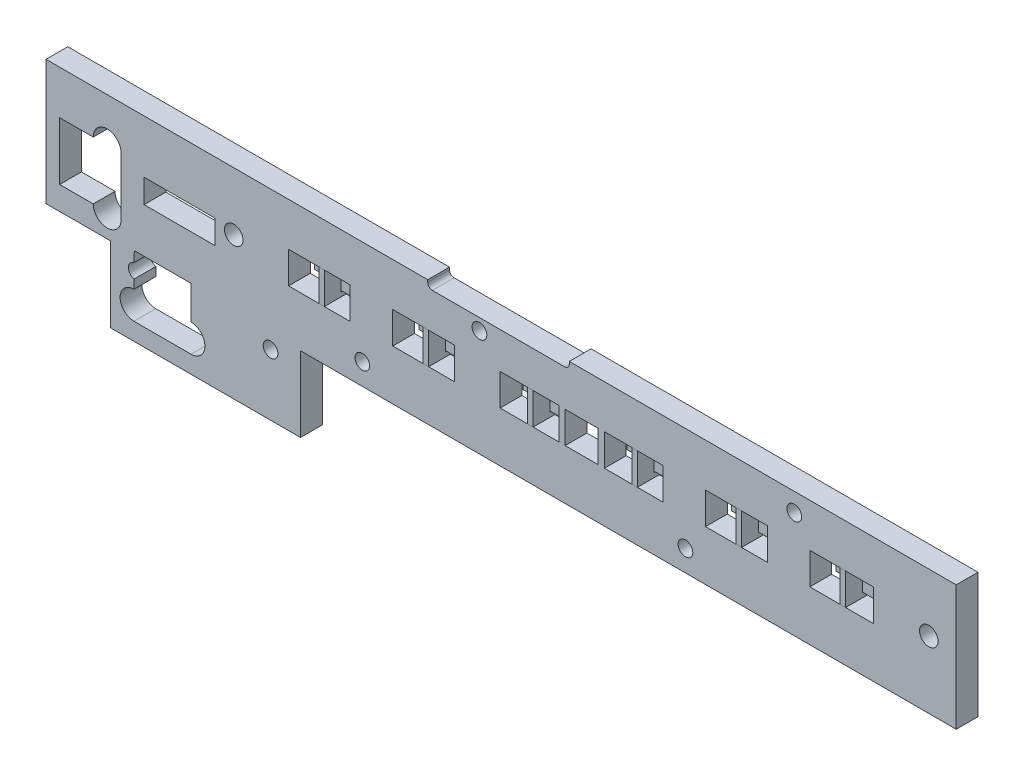
SolidWorks part; units mm, degrees
ref_plane "Front Plane" through (0, 0, 0) normal (0, 0, 1) x (1, 0, 0)
ref_plane "Top Plane" through (0, 0, 0) normal (0, 1, 0) x (1, 0, 0)
ref_plane "Right Plane" through (0, 0, 0) normal (1, 0, 0) x (0, 0, -1)
sketch "Sketch1" plane through (0, 0, 0) normal (0, 0, 1) x (1, 0, 0)
  line L1 (-97.5199, -40.1399) -> (-95.437, -40.1399)
  line L2 (-97.5199, -40.1399) -> (-97.5199, -41.3128)
  line L3 (-97.5199, -41.3128) -> (-95.437, -41.3128)
  line L4 (-95.437, -40.1399) -> (-95.437, -41.3128)
  line L5 (-92.4399, -40.1399) -> (-90.3585, -40.1399)
  line L6 (-92.4399, -40.1399) -> (-92.4399, -41.3128)
  line L7 (-92.4399, -41.3128) -> (-90.3585, -41.3128)
  line L8 (-90.3585, -40.1399) -> (-90.3585, -41.3128)
  line L9 (-75.0363, -40.1399) -> (-72.9606, -40.1399)
  line L10 (-75.0363, -40.1399) -> (-75.0363, -41.3128)
  line L11 (-75.0363, -41.3128) -> (-72.9606, -41.3128)
  line L12 (-72.9606, -40.1399) -> (-72.9606, -41.3128)
  line L13 (-69.9609, -40.1399) -> (-67.8729, -40.1399)
  line L14 (-69.9609, -40.1399) -> (-69.9609, -41.3128)
  line L15 (-69.9609, -41.3128) -> (-67.8729, -41.3128)
  line L16 (-67.8729, -40.1399) -> (-67.8729, -41.3128)
  line L17 (-52.5418, -40.1399) -> (-50.4863, -40.1399)
  line L18 (-52.5418, -40.1399) -> (-52.5418, -41.3128)
  line L19 (-52.5418, -41.3128) -> (-50.4863, -41.3128)
  line L20 (-50.4863, -40.1399) -> (-50.4863, -41.3128)
  line L21 (-47.4819, -40.1399) -> (-45.3964, -40.1399)
  line L22 (-47.4819, -40.1399) -> (-47.4819, -41.3128)
  line L23 (-47.4819, -41.3128) -> (-45.3964, -41.3128)
  line L24 (-45.3964, -40.1399) -> (-45.3964, -41.3128)
  line L25 (-30.0829, -40.1399) -> (-27.9975, -40.1399)
  line L26 (-30.0829, -40.1399) -> (-30.0829, -41.3128)
  line L27 (-30.0829, -41.3128) -> (-27.9975, -41.3128)
  line L28 (-27.9975, -40.1399) -> (-27.9975, -41.3128)
  line L29 (-24.8733, -40.1399) -> (-22.7944, -40.1399)
  line L30 (-24.8733, -40.1399) -> (-24.8733, -41.3128)
  line L31 (-24.8733, -41.3128) -> (-22.7944, -41.3128)
  line L32 (-22.7944, -40.1399) -> (-22.7944, -41.3128)
  line L33 (-7.4594, -40.1399) -> (-5.3743, -40.1399)
  line L34 (-7.4594, -40.1399) -> (-7.4594, -41.3128)
  line L35 (-7.4594, -41.3128) -> (-5.3743, -41.3128)
  line L36 (-5.3743, -40.1399) -> (-5.3743, -41.3128)
  line L37 (-2.3715, -40.1399) -> (-0.2978, -40.1399)
  line L38 (-2.3715, -40.1399) -> (-2.3715, -41.3128)
  line L39 (-2.3715, -41.3128) -> (-0.2978, -41.3128)
  line L40 (-0.2978, -40.1399) -> (-0.2978, -41.3128)
  line L41 (14.9285, -40.1399) -> (16.9943, -40.1399)
  line L42 (14.9285, -40.1399) -> (14.9285, -41.3128)
  line L43 (14.9285, -41.3128) -> (16.9943, -41.3128)
  line L44 (16.9943, -40.1399) -> (16.9943, -41.3128)
  line L45 (20.1255, -40.1399) -> (22.2118, -40.1399)
  line L46 (20.1255, -40.1399) -> (20.1255, -41.3128)
  line L47 (20.1255, -41.3128) -> (22.2118, -41.3128)
  line L48 (22.2118, -40.1399) -> (22.2118, -41.3128)
  line L49 (20.4423, -42.9104) -> (22.0728, -42.9104)
  line L50 (20.4423, -42.9104) -> (20.4423, -43.6338)
  line L51 (20.4423, -43.6338) -> (22.0728, -43.6338)
  line L52 (22.0728, -42.9104) -> (22.0728, -43.6338)
  line L53 (15.3323, -42.9104) -> (16.9094, -42.9104)
  line L54 (15.3323, -42.9104) -> (15.3323, -43.6338)
  line L55 (15.3323, -43.6338) -> (16.9094, -43.6338)
  line L56 (16.9094, -42.9104) -> (16.9094, -43.6338)
  line L57 (-7.183, -42.9104) -> (-5.7103, -42.9104)
  line L58 (-7.183, -42.9104) -> (-7.183, -43.6338)
  line L59 (-7.183, -43.6338) -> (-5.7103, -43.6338)
  line L60 (-5.7103, -42.9104) -> (-5.7103, -43.6338)
  line L61 (-2.1219, -42.9104) -> (-0.6974, -42.9104)
  line L62 (-2.1219, -42.9104) -> (-2.1219, -43.6338)
  line L63 (-2.1219, -43.6338) -> (-0.6974, -43.6338)
  line L64 (-0.6974, -42.9104) -> (-0.6974, -43.6338)
  line L65 (-24.6153, -42.9104) -> (-23.1268, -42.9104)
  line L66 (-24.6153, -42.9104) -> (-24.6153, -43.6338)
  line L67 (-24.6153, -43.6338) -> (-23.1268, -43.6338)
  line L68 (-23.1268, -42.9104) -> (-23.1268, -43.6338)
  line L69 (-29.8441, -42.9104) -> (-28.3135, -42.9104)
  line L70 (-29.8441, -42.9104) -> (-29.8441, -43.6338)
  line L71 (-29.8441, -43.6338) -> (-28.3135, -43.6338)
  line L72 (-28.3135, -42.9104) -> (-28.3135, -43.6338)
  line L73 (-47.2091, -42.9104) -> (-45.7145, -42.9104)
  line L74 (-47.2091, -42.9104) -> (-47.2091, -43.6338)
  line L75 (-47.2091, -43.6338) -> (-45.7145, -43.6338)
  line L76 (-45.7145, -42.9104) -> (-45.7145, -43.6338)
  line L77 (-52.2861, -42.9104) -> (-50.7652, -42.9104)
  line L78 (-52.2861, -42.9104) -> (-52.2861, -43.6338)
  line L79 (-52.2861, -43.6338) -> (-50.7652, -43.6338)
  line L80 (-50.7652, -42.9104) -> (-50.7652, -43.6338)
  line L81 (-74.7983, -42.9104) -> (-73.2628, -42.9104)
  line L82 (-74.7983, -42.9104) -> (-74.7983, -43.6338)
  line L83 (-74.7983, -43.6338) -> (-73.2628, -43.6338)
  line L84 (-73.2628, -42.9104) -> (-73.2628, -43.6338)
  line L85 (-69.6691, -42.9104) -> (-68.1499, -42.9104)
  line L86 (-69.6691, -42.9104) -> (-69.6691, -43.6338)
  line L87 (-69.6691, -43.6338) -> (-68.1499, -43.6338)
  line L88 (-68.1499, -42.9104) -> (-68.1499, -43.6338)
  line L89 (-97.2136, -42.9104) -> (-95.6835, -42.9104)
  line L90 (-97.2136, -42.9104) -> (-97.2136, -43.6338)
  line L91 (-97.2136, -43.6338) -> (-95.6835, -43.6338)
  line L92 (-95.6835, -42.9104) -> (-95.6835, -43.6338)
  line L93 (-92.0424, -42.9104) -> (-90.6479, -42.9104)
  line L94 (-92.0424, -42.9104) -> (-92.0424, -43.6338)
  line L95 (-92.0424, -43.6338) -> (-90.6479, -43.6338)
  line L96 (-90.6479, -42.9104) -> (-90.6479, -43.6338)
  line L97 (-40.9561, -23.8413) -> (-37.9731, -23.8413)
  line L98 (-40.9561, -23.8413) -> (-40.9561, -26.801)
  line L99 (-40.9561, -26.801) -> (-37.9731, -26.801)
  line L100 (-37.9731, -23.8413) -> (-37.9731, -26.801)
  line L101 (-27.6683, -24.3836) -> (-19.7589, -24.3836)
  line L102 (-27.6683, -24.3836) -> (-27.6683, -26.304)
  line L103 (-27.6683, -26.304) -> (-19.7589, -26.304)
  line L104 (-19.7589, -24.3836) -> (-19.7589, -26.304)
  line L105 (-10.3004, -24.5939) -> (-8.2388, -24.5939)
  line L106 (-10.3004, -24.5939) -> (-10.3004, -25.8839)
  line L107 (-10.3004, -25.8839) -> (-8.2388, -25.8839)
  line L108 (-8.2388, -24.5939) -> (-8.2388, -25.8839)
  line L109 (-108.8964, -23.5079) -> (-98.4981, -23.5079)
  line L110 (-108.8964, -23.5079) -> (-108.8964, -12.9295)
  line L111 (-108.8964, -12.9295) -> (-98.4981, -12.9295)
  line L112 (-98.4981, -23.5079) -> (-98.4981, -12.9295)
  line L113 (-96.9584, -23.5079) -> (-86.5337, -23.5079)
  line L114 (-96.9584, -23.5079) -> (-96.9584, -12.9295)
  line L115 (-96.9584, -12.9295) -> (-86.5337, -12.9295)
  line L116 (-86.5337, -23.5079) -> (-86.5337, -12.9295)
  line L118 (4.3836, -57.8006) -> (14.3835, -57.8006)
  line L119 (4.3836, -57.8006) -> (4.3836, -67.7079)
  line L120 (4.3836, -67.7079) -> (14.3835, -67.7079)
  line L121 (14.3835, -57.8006) -> (14.3835, -67.7079)
  line L122 (-95.437, -40.7263) -> (-92.4399, -40.7263) construction
  line L123 (-118.2514, 77.6271) -> (84.9486, 77.6271)
  line L124 (-118.2514, 77.6271) -> (-118.2514, -74.7729)
  line L125 (-118.2514, -74.7729) -> (84.9486, -74.7729)
  line L126 (84.9486, 77.6271) -> (84.9486, -74.7729)
  line L127 (-93.9384, -39.7294) -> (-93.9384, -44.0708) construction
  circle A0 centre (-26.6844, -66.6449) radius 1.981
  circle A1 centre (37.6626, -40.7409) radius 2
  circle A2 centre (7.2246, -15.4639) radius 1.981
  circle A3 centre (34.1156, -16.8649) radius 2
  circle A4 centre (62.0556, -16.8649) radius 2
  circle A5 centre (78.5986, -14.4479) radius 1.981
  circle A6 centre (-112.3324, -40.7459) radius 2
  circle A7 centre (-111.9014, -68.4229) radius 1.981
sketch "Sketch26" plane through (0, 0, 0) normal (0, 0, 1) x (1, 0, 0)
  line L0 (-347.4806, 59.2876) -> (-347.7663, 59.0018)
  line L5 (-126.8633, -41.6631) -> (-126.2918, -41.6631)
  line L6 (-126.2918, -41.6631) -> (-126.0061, -41.9489)
  line L8 (-126.0061, -41.9489) -> (-126.0061, -42.5204)
  line L12 (-126.0061, -42.5204) -> (-126.2918, -42.8061)
  line L14 (-126.2918, -42.8061) -> (-126.8633, -42.8061)
  line L16 (-126.8633, -42.8061) -> (-127.1491, -42.5204)
  line L17 (-127.1491, -42.5204) -> (-127.1491, -41.9489)
  line L18 (-127.1491, -41.9489) -> (-126.8633, -41.6631)
  line L19 (-124.3233, -41.6631) -> (-123.7518, -41.6631)
  line L20 (-123.7518, -41.6631) -> (-123.4661, -41.9489)
  line L21 (-123.4661, -41.9489) -> (-123.4661, -42.5204)
  line L22 (-123.4661, -42.5204) -> (-123.7518, -42.8061)
  line L23 (-123.7518, -42.8061) -> (-124.3223, -42.8061)
  line L24 (-124.3223, -42.8061) -> (-124.6091, -42.5204)
  line L25 (-124.6091, -42.5204) -> (-124.6091, -41.9489)
  line L26 (-124.6091, -41.9489) -> (-124.3233, -41.6631)
  line L28 (-121.7833, -41.6631) -> (-121.2118, -41.6631)
  line L29 (-121.2118, -41.6631) -> (-120.9261, -41.9489)
  line L30 (-120.9261, -41.9489) -> (-120.9261, -42.5204)
  line L32 (-120.9261, -42.5204) -> (-121.2118, -42.8061)
  line L34 (-121.2118, -42.8061) -> (-121.7833, -42.8061)
  line L35 (-121.7833, -42.8061) -> (-122.0691, -42.5204)
  line L36 (-122.0691, -42.5204) -> (-122.0691, -41.9489)
  line L37 (-122.0691, -41.9489) -> (-121.7833, -41.6631)
  circle A0 centre (-112.3486, -40.7056) radius 2
  circle A1 centre (37.6464, -40.7106) radius 2
sketch "Sketch2" plane through (0, 0, 0) normal (0, 0, 1) x (1, 0, 0)
  line L1 (-98.5701, -39.3785) -> (-95.299, -39.3785)
  line L2 (-98.5701, -39.3785) -> (-98.5701, -42.1823)
  line L3 (-98.5701, -42.1823) -> (-95.299, -42.1823)
  line L4 (-95.299, -39.3785) -> (-95.299, -42.1823)
  line L5 (-94.4404, -38.3353) -> (-89.1697, -38.3353)
  line L6 (-94.4404, -38.3353) -> (-94.4404, -43.2582)
  line L7 (-94.4404, -43.2582) -> (-89.1697, -43.2582)
  line L8 (-89.1697, -38.3353) -> (-89.1697, -43.2582)
  line L9 (-76.0896, -39.3785) -> (-72.8441, -39.3785)
  line L10 (-76.0896, -39.3785) -> (-76.0896, -42.1823)
  line L11 (-76.0896, -42.1823) -> (-72.8441, -42.1823)
  line L12 (-72.8441, -39.3785) -> (-72.8441, -42.1823)
  line L13 (-71.9827, -38.3353) -> (-66.6627, -38.3353)
  line L14 (-71.9827, -38.3353) -> (-71.9827, -43.2582)
  line L15 (-71.9827, -43.2582) -> (-66.6627, -43.2582)
  line L16 (-66.6627, -38.3353) -> (-66.6627, -43.2582)
  line L17 (-53.6202, -39.3785) -> (-50.3601, -39.3785)
  line L18 (-53.6202, -39.3785) -> (-53.6202, -42.1823)
  line L19 (-53.6202, -42.1823) -> (-50.3601, -42.1823)
  line L20 (-50.3601, -39.3785) -> (-50.3601, -42.1823)
  line L21 (-49.5184, -38.3353) -> (-44.1883, -38.3353)
  line L22 (-49.5184, -38.3353) -> (-49.5184, -43.2582)
  line L23 (-49.5184, -43.2582) -> (-44.1883, -43.2582)
  line L24 (-44.1883, -38.3353) -> (-44.1883, -43.2582)
  line L25 (-31.1243, -39.3785) -> (-27.8326, -39.3785)
  line L26 (-31.1243, -39.3785) -> (-31.1243, -42.1823)
  line L27 (-31.1243, -42.1823) -> (-27.8326, -42.1823)
  line L28 (-27.8326, -39.3785) -> (-27.8326, -42.1823)
  line L29 (-27.0038, -38.3353) -> (-21.7574, -38.3353)
  line L30 (-27.0038, -38.3353) -> (-27.0038, -43.2582)
  line L31 (-27.0038, -43.2582) -> (-21.7574, -43.2582)
  line L32 (-21.7574, -38.3353) -> (-21.7574, -43.2582)
  line L33 (-8.6176, -39.3785) -> (-5.1948, -39.3785)
  line L34 (-8.6176, -39.3785) -> (-8.6176, -42.3426)
  line L35 (-8.6176, -42.3426) -> (-5.1948, -42.3426)
  line L36 (-5.1948, -39.3785) -> (-5.1948, -42.3426)
  line L37 (-4.443, -38.4846) -> (0.8593, -38.4846)
  line L38 (-4.443, -38.4846) -> (-4.443, -43.3911)
  line L39 (-4.443, -43.3911) -> (0.8593, -43.3911)
  line L40 (0.8593, -38.4846) -> (0.8593, -43.3911)
  line L41 (13.9171, -39.6123) -> (17.1222, -39.6123)
  line L42 (13.9171, -39.6123) -> (13.9171, -42.3426)
  line L43 (13.9171, -42.3426) -> (17.1222, -42.3426)
  line L44 (17.1222, -39.6123) -> (17.1222, -42.3426)
  line L45 (18.0465, -38.4846) -> (23.3015, -38.4846)
  line L46 (18.0465, -38.4846) -> (18.0465, -43.3911)
  line L47 (18.0465, -43.3911) -> (23.3015, -43.3911)
  line L48 (23.3015, -38.4846) -> (23.3015, -43.3911)
  circle A0 centre (-112.3324, -40.7459) radius 2
  circle A1 centre (37.6626, -40.7409) radius 2
sketch "Sketch3" plane through (0, 0, 0) normal (0, 0, 1) x (1, 0, 0)
  line L0 (-92.4239, -40.172) -> (-90.3528, -40.172)
  line L1 (-117.3165, -28.7781) -> (77.6835, -28.7781)
  line L2 (-117.3165, -28.7781) -> (-117.3165, -54.7781)
  line L3 (-117.3165, -54.7781) -> (77.6835, -54.7781)
  line L4 (77.6835, -28.7781) -> (77.6835, -54.7781)
  line L5 (-97.501, -40.1688) -> (-95.4364, -40.1688)
  line L6 (-97.501, -40.1688) -> (-97.501, -41.3458)
  line L7 (-97.501, -41.3458) -> (-95.4364, -41.3458)
  line L8 (-95.4364, -40.1688) -> (-95.4364, -41.3458)
  line L9 (-92.4239, -40.172) -> (-92.4239, -41.3431)
  line L10 (-92.4239, -41.3431) -> (-90.3528, -41.3431)
  line L11 (-90.3528, -40.172) -> (-90.3528, -41.3431)
  line L12 (-75.0249, -40.172) -> (-72.9538, -40.172)
  line L13 (-75.0249, -40.172) -> (-75.0249, -41.3431)
  line L14 (-75.0249, -41.3431) -> (-72.9538, -41.3431)
  line L15 (-72.9538, -40.172) -> (-72.9538, -41.3431)
  line L16 (-69.9449, -40.172) -> (-67.8738, -40.172)
  line L17 (-69.9449, -40.172) -> (-69.9449, -41.3431)
  line L18 (-69.9449, -41.3431) -> (-67.8738, -41.3431)
  line L19 (-67.8738, -40.172) -> (-67.8738, -41.3431)
  line L20 (-52.5459, -40.172) -> (-50.4749, -40.172)
  line L21 (-52.5459, -40.172) -> (-52.5459, -41.3431)
  line L22 (-52.5459, -41.3431) -> (-50.4749, -41.3431)
  line L23 (-50.4749, -40.172) -> (-50.4749, -41.3431)
  line L24 (20.0981, -40.172) -> (22.1692, -40.172)
  line L25 (20.0981, -40.172) -> (20.0981, -41.3431)
  line L26 (20.0981, -41.3431) -> (22.1692, -41.3431)
  line L27 (22.1692, -40.172) -> (22.1692, -41.3431)
  line L28 (14.8911, -40.172) -> (16.9622, -40.172)
  line L29 (14.8911, -40.172) -> (14.8911, -41.3431)
  line L30 (14.8911, -41.3431) -> (16.9622, -41.3431)
  line L31 (16.9622, -40.172) -> (16.9622, -41.3431)
  line L32 (-7.4609, -40.172) -> (-5.3898, -40.172)
  line L33 (-7.4609, -40.172) -> (-7.4609, -41.3431)
  line L34 (-7.4609, -41.3431) -> (-5.3898, -41.3431)
  line L35 (-5.3898, -40.172) -> (-5.3898, -41.3431)
  line L36 (-2.3809, -40.172) -> (-0.3098, -40.172)
  line L37 (-2.3809, -40.172) -> (-2.3809, -41.3431)
  line L38 (-2.3809, -41.3431) -> (-0.3098, -41.3431)
  line L39 (-0.3098, -40.172) -> (-0.3098, -41.3431)
  line L40 (-30.0669, -40.172) -> (-27.9959, -40.172)
  line L41 (-30.0669, -40.172) -> (-30.0669, -41.3431)
  line L42 (-30.0669, -41.3431) -> (-27.9959, -41.3431)
  line L43 (-27.9959, -40.172) -> (-27.9959, -41.3431)
  line L44 (-24.8599, -40.172) -> (-22.7889, -40.172)
  line L45 (-24.8599, -40.172) -> (-24.8599, -41.3431)
  line L46 (-24.8599, -41.3431) -> (-22.7889, -41.3431)
  line L47 (-22.7889, -40.172) -> (-22.7889, -41.3431)
  line L48 (-47.4659, -40.172) -> (-45.3838, -40.172)
  line L49 (-47.4659, -40.172) -> (-47.4659, -41.359)
  line L50 (-47.4659, -41.359) -> (-45.3838, -41.359)
  line L51 (-45.3838, -40.172) -> (-45.3838, -41.359)
  line L53 (-97.7776, -39.3992) -> (-94.4929, -39.3992)
  line L54 (-97.7776, -39.3992) -> (-97.7776, -42.1711)
  line L55 (-97.7776, -42.1711) -> (-94.4929, -42.1711)
  line L56 (-94.4929, -39.3992) -> (-94.4929, -42.1711)
  line L57 (-93.627, -38.3011) -> (-88.3259, -38.3011)
  line L58 (-93.627, -38.3011) -> (-93.627, -43.2774)
  line L59 (-93.627, -43.2774) -> (-88.3259, -43.2774)
  line L60 (-88.3259, -38.3011) -> (-88.3259, -43.2774)
  line L65 (-75.2412, -39.3992) -> (-72.0308, -39.3992)
  line L66 (-75.2412, -39.3992) -> (-75.2412, -42.1711)
  line L67 (-75.2412, -42.1711) -> (-72.0308, -42.1711)
  line L68 (-72.0308, -39.3992) -> (-72.0308, -42.1711)
  line L69 (-71.1042, -38.3011) -> (-65.8448, -38.3011)
  line L70 (-71.1042, -38.3011) -> (-71.1042, -43.2774)
  line L71 (-71.1042, -43.2774) -> (-65.8448, -43.2774)
  line L72 (-65.8448, -38.3011) -> (-65.8448, -43.2774)
  line L73 (-52.7841, -39.3992) -> (-49.488, -39.3992)
  line L74 (-52.7841, -39.3992) -> (-52.7841, -42.1711)
  line L75 (-52.7841, -42.1711) -> (-49.488, -42.1711)
  line L76 (-49.488, -39.3992) -> (-49.488, -42.1711)
  line L77 (-48.6647, -38.3011) -> (-43.2769, -38.3011)
  line L78 (-48.6647, -38.3011) -> (-48.6647, -43.2774)
  line L79 (-48.6647, -43.2774) -> (-43.2769, -43.2774)
  line L80 (-43.2769, -38.3011) -> (-43.2769, -43.2774)
  line L81 (-30.2826, -39.3992) -> (-26.9885, -39.3992)
  line L82 (-30.2826, -39.3992) -> (-30.2826, -42.1711)
  line L83 (-30.2826, -42.1711) -> (-26.9885, -42.1711)
  line L84 (-26.9885, -39.3992) -> (-26.9885, -42.1711)
  line L85 (-26.1225, -38.3011) -> (-20.7991, -38.3011)
  line L86 (-26.1225, -38.3011) -> (-26.1225, -43.2774)
  line L87 (-26.1225, -43.2774) -> (-20.7991, -43.2774)
  line L88 (-20.7991, -38.3011) -> (-20.7991, -43.2774)
  line L89 (-7.7852, -39.3992) -> (-4.5112, -39.3992)
  line L90 (-7.7852, -39.3992) -> (-7.7852, -42.1711)
  line L91 (-7.7852, -42.1711) -> (-4.5112, -42.1711)
  line L92 (-4.5112, -39.3992) -> (-4.5112, -42.1711)
  line L93 (-3.6465, -38.3011) -> (1.6758, -38.3011)
  line L94 (-3.6465, -38.3011) -> (-3.6465, -43.2774)
  line L95 (-3.6465, -43.2774) -> (1.6758, -43.2774)
  line L96 (1.6758, -38.3011) -> (1.6758, -43.2774)
  line L97 (14.7148, -39.3992) -> (17.9992, -39.3992)
  line L98 (14.7148, -39.3992) -> (14.7148, -42.1711)
  line L99 (14.7148, -42.1711) -> (17.9992, -42.1711)
  line L100 (17.9992, -39.3992) -> (17.9992, -42.1711)
  line L101 (18.8348, -38.3011) -> (24.1792, -38.3011)
  line L102 (18.8348, -38.3011) -> (18.8348, -43.2774)
  line L103 (18.8348, -43.2774) -> (24.1792, -43.2774)
  line L104 (24.1792, -38.3011) -> (24.1792, -43.2774)
  circle A0 centre (-112.3165, -40.7781) radius 2
  circle A1 centre (37.6835, -40.7781) radius 2
extrude "Boss-Extrude1" add sketch "Sketch3" along normal blind 0.5 contours L60 L57 L58 L59 L0 L11 L10 L9 | L56 L53 L54 L55 L5 L8 L7 L6 | L68 L65 L66 L67 L12 L15 L14 L13 | L72 L69 L70 L71 L16 L19 L18 L17 | L76 L73 L74 L75 L20 L23 L22 L21 | L80 L77 L78 L79 L48 L51 L50 L49 | L84 L81 L82 L83 L40 L43 L42 L41 | L88 L85 L86 L87 L44 L47 L46 L45 | L92 L89 L90 L91 L32 L35 L34 L33 | L96 L93 L94 L95 L36 L39 L38 L37 | L100 L97 L98 L99 L28 L31 L30 L29 | L104 L101 L102 L103 L24 L27 L26 L25
extrude "Boss-Extrude2" add sketch "Sketch2" along normal blind 1 contours L2 L1 L4 L3 | L6 L5 L8 L7 | L10 L9 L12 L11 | L14 L13 L16 L15 | L18 L17 L20 L19 | L22 L21 L24 L23 | L26 L25 L28 L27 | L30 L29 L32 L31 | L34 L33 L36 L35 | L38 L37 L40 L39 | L42 L41 L44 L43 | L46 L45 L48 L47
sketch "Sketch27" plane through (0, 0, 0) normal (0, 0, 1) x (1, 0, 0)
  line L6 (-127.1316, -41.9504) -> (-126.8458, -41.6646)
  line L7 (-126.8458, -41.6646) -> (-126.2743, -41.6646)
  line L8 (-126.2743, -41.6646) -> (-125.9886, -41.9504)
  line L9 (-125.9886, -41.9504) -> (-125.9886, -42.5219)
  line L10 (-125.9886, -42.5219) -> (-126.2743, -42.8076)
  line L11 (-126.2743, -42.8076) -> (-126.8458, -42.8076)
  line L12 (-126.8458, -42.8076) -> (-127.1316, -42.5219)
  line L13 (-127.1316, -42.5219) -> (-127.1316, -41.9504)
  line L14 (-124.3058, -41.6646) -> (-123.7343, -41.6646)
  line L15 (-123.7343, -41.6646) -> (-123.4486, -41.9504)
  line L16 (-123.4486, -41.9504) -> (-123.4486, -42.5219)
  line L17 (-123.4486, -42.5219) -> (-123.7343, -42.8076)
  line L18 (-123.7343, -42.8076) -> (-124.3058, -42.8076)
  line L19 (-124.3058, -42.8076) -> (-124.5916, -42.5219)
  line L20 (-124.5916, -42.5219) -> (-124.5916, -41.9504)
  line L21 (-124.5916, -41.9504) -> (-124.3058, -41.6646)
  line L22 (-122.0516, -41.9504) -> (-121.7658, -41.6646)
  line L23 (-121.7658, -41.6646) -> (-121.1943, -41.6646)
  line L24 (-121.1943, -41.6646) -> (-120.9086, -41.9504)
  line L25 (-120.9086, -41.9504) -> (-120.9086, -42.5219)
  line L26 (-120.9086, -42.5219) -> (-121.1943, -42.8076)
  line L27 (-121.1943, -42.8076) -> (-121.7658, -42.8076)
  line L28 (-121.7658, -42.8076) -> (-122.0516, -42.5219)
  line L29 (-122.0516, -42.5219) -> (-122.0516, -41.9504)
  circle A1 centre (-112.3361, -40.7121) radius 2
  circle A2 centre (37.6639, -40.7121) radius 2
sketch "Sketch4" plane through (0, 0, 0) normal (0, 0, 1) x (1, 0, 0)
  line L0 (-39.4646, -26.801) -> (-138.2561, -26.801) construction
  line L1 (-40.9561, -26.801) -> (-37.9731, -26.801) construction
  line L2 (-118.2514, 77.6271) -> (-118.2514, -74.7729) construction
  line L3 (-39.4646, -26.801) -> (84.9486, -26.801) construction
  line L5 (-118.2514, -57.8006) -> (84.9486, -57.8006) construction
  line L6 (-88.3259, -38.3011) -> (-118.2514, -38.3011) construction
  line L7 (-88.3259, -38.3011) -> (84.9486, -38.3011) construction
  line L8 (23.3015, -43.3911) -> (84.9486, -43.3911) construction
  line L9 (23.3015, -43.3911) -> (-118.2514, -43.3911) construction
  line L10 (-97.2136, -43.6338) -> (-118.2514, -43.6338) construction
  line L11 (-97.2136, -43.6338) -> (84.9486, -43.6338) construction
  line L12 (-114.3324, -40.7459) -> (-118.2514, -40.7459) construction
  line L13 (-110.3324, -40.7459) -> (-98.5701, -40.7804) construction
  line L14 (-98.5701, -39.3785) -> (-98.5701, -42.1823) construction
  line L15 (35.6626, -40.7409) -> (24.2584, -40.7409) construction
  line L16 (39.6626, -40.7409) -> (44.6626, -40.7409) construction
  line L17 (-24.3806, -38.3353) -> (-24.3806, -28.3353) construction
  line L18 (-27.0038, -38.3353) -> (-21.7574, -38.3353) construction
  line L19 (-20.7991, -38.3011) -> (-20.7991, -31.3011) construction
  line L20 (-24.3806, -43.6338) -> (-24.3806, -53.6338) construction
  line L21 (-20.7991, -43.6338) -> (-20.7991, -50.6338) construction
  line L22 (-31.1243, -40.7804) -> (-34.1243, -40.7804) construction
  line L23 (-31.1243, -39.3785) -> (-31.1243, -42.1823) construction
  line L24 (-20.7991, -40.7893) -> (-17.7991, -40.7893) construction
  line L25 (-20.7991, -38.3011) -> (-20.7991, -43.2774) construction
  line L26 (-43.2769, -40.7893) -> (-40.2769, -40.7893) construction
  line L27 (-43.2769, -38.3011) -> (-43.2769, -43.2774) construction
  line L28 (-53.6202, -40.7804) -> (-56.6202, -40.7804) construction
  line L29 (-53.6202, -39.3785) -> (-53.6202, -42.1823) construction
  line L30 (-8.6176, -40.8606) -> (-11.6176, -40.8606) construction
  line L31 (-8.6176, -39.3785) -> (-8.6176, -42.3426) construction
  line L32 (1.6758, -40.7893) -> (4.6755, -40.8345) construction
  line L33 (1.6758, -38.3011) -> (1.6758, -43.2774) construction
  line L34 (13.9171, -40.9774) -> (10.9171, -40.9774) construction
  line L35 (13.9171, -39.6123) -> (13.9171, -42.3426) construction
  line L36 (24.1792, -40.218) -> (27.1792, -40.218) construction
  line L37 (24.1792, -38.3011) -> (24.1792, -43.2774) construction
  line L38 (-98.5701, -39.9285) -> (-101.5701, -39.9285) construction
  line L39 (-88.3259, -40.7893) -> (-85.3259, -40.7893) construction
  line L40 (-88.3259, -38.3011) -> (-88.3259, -43.2774) construction
  line L41 (-76.0896, -40.7804) -> (-79.0896, -40.7804) construction
  line L42 (-76.0896, -39.3785) -> (-76.0896, -42.1823) construction
  line L43 (-65.8448, -40.7893) -> (-62.8455, -40.8558) construction
  line L44 (-65.8448, -38.3011) -> (-65.8448, -43.2774) construction
  line L46 (-17.7991, -31.3011) -> (-34.1243, -31.3011)
  line L47 (-17.7991, -31.3011) -> (-17.7991, -50.9192)
  line L48 (-17.7991, -50.9192) -> (-34.1243, -50.9192)
  line L49 (-34.1243, -31.3011) -> (-34.1243, -50.9192)
  line L50 (-40.2769, -31.3011) -> (-56.6202, -31.3011)
  line L51 (-40.2769, -31.3011) -> (-40.2769, -50.6338)
  line L52 (-40.2769, -50.6338) -> (-56.6202, -50.6338)
  line L53 (-56.6202, -31.3011) -> (-56.6202, -50.6338)
  line L54 (-62.8455, -31.3011) -> (-79.0896, -31.3011)
  line L55 (-62.8455, -31.3011) -> (-62.8455, -50.6338)
  line L56 (-62.8455, -50.6338) -> (-79.0896, -50.6338)
  line L57 (-79.0896, -31.3011) -> (-79.0896, -50.6338)
  line L58 (-85.3259, -31.3011) -> (-101.5701, -31.3011)
  line L59 (-85.3259, -31.3011) -> (-85.3259, -50.6338)
  line L60 (-85.3259, -50.6338) -> (-101.5701, -50.6338)
  line L61 (-101.5701, -31.3011) -> (-101.5701, -50.6338)
  line L66 (-11.6176, -31.3011) -> (4.6755, -31.3011)
  line L67 (-11.6176, -31.3011) -> (-11.6176, -50.9192)
  line L68 (-11.6176, -50.9192) -> (4.6755, -50.9192)
  line L69 (4.6755, -31.3011) -> (4.6755, -50.9192)
  line L70 (10.9171, -31.3011) -> (27.1792, -31.3011)
  line L71 (10.9171, -31.3011) -> (10.9171, -50.9192)
  line L72 (10.9171, -50.9192) -> (27.1792, -50.9192)
  line L73 (27.1792, -31.3011) -> (27.1792, -50.9192)
  line L74 (-118.2514, -28.2107) -> (43.5826, -28.2107)
  line L77 (43.5826, -28.2107) -> (43.5826, -55.2138)
  line L79 (-152.8489, -71.4364) -> (-152.8489, -28.2107)
  line L80 (-152.8489, -71.4364) -> (-97.9233, -71.4364)
  line L81 (43.5826, -55.2138) -> (-97.9233, -55.2138)
  line L82 (-97.9233, -55.2138) -> (-97.9233, -71.4364)
  line L83 (-152.8489, -28.2107) -> (-118.2514, -28.2107)
  circle A0 centre (-112.3324, -40.7459) radius 2
  circle A1 centre (37.6626, -40.7409) radius 2
  circle A2 centre (-112.3324, -40.7459) radius 2
  circle A3 centre (37.6626, -40.7409) radius 2
  point P127 (-98.406, -55.2138)
  point P128 (-118.2514, -35.8832)
extrude "Boss-Extrude3" add sketch "Sketch4" along normal blind 4.7 separate body contours L74 L77 L81 L82 L80 L79 L83
sketch "Sketch6" plane through (0, 0, 0) normal (0, 0, 1) x (1, 0, 0)
  line L3 (-39.4646, -26.801) -> (84.9486, -26.801) construction
  line L12 (-114.3324, -40.7459) -> (-118.2514, -40.7459) construction
  line L16 (39.6626, -40.7409) -> (44.6626, -40.7409) construction
  line L46 (-19.6893, -37.55) -> (-32.3365, -37.55)
  line L47 (-19.6893, -37.55) -> (-19.6893, -44.39)
  line L48 (-19.6893, -44.39) -> (-32.3365, -44.39)
  line L49 (-32.3365, -37.55) -> (-32.3365, -44.39)
  line L50 (-42.1847, -37.55) -> (-54.8514, -37.55)
  line L51 (-42.1847, -37.55) -> (-42.1847, -44.39)
  line L52 (-42.1847, -44.39) -> (-54.8514, -44.39)
  line L53 (-54.8514, -37.55) -> (-54.8514, -44.39)
  line L54 (-64.6621, -37.55) -> (-78.0238, -37.55)
  line L55 (-64.6621, -37.55) -> (-64.6621, -44.39)
  line L56 (-64.6621, -44.39) -> (-78.0238, -44.39)
  line L57 (-78.0238, -37.55) -> (-78.0238, -44.39)
  line L58 (-87.1961, -37.55) -> (-100.5057, -37.55)
  line L59 (-87.1961, -37.55) -> (-87.1961, -44.39)
  line L60 (-87.1961, -44.39) -> (-100.5057, -44.39)
  line L61 (-100.5057, -37.55) -> (-100.5057, -44.39)
  line L66 (-10.5159, -37.55) -> (2.8408, -37.55)
  line L67 (-10.5159, -37.55) -> (-10.5159, -44.39)
  line L68 (-10.5159, -44.39) -> (2.8408, -44.39)
  line L69 (2.8408, -37.55) -> (2.8408, -44.39)
  line L70 (11.9869, -37.55) -> (25.7171, -37.55)
  line L71 (11.9869, -37.55) -> (11.9869, -44.39)
  line L72 (11.9869, -44.39) -> (25.7171, -44.39)
  line L73 (25.7171, -37.55) -> (25.7171, -44.39)
  line L74 (-118.2514, -28.3353) -> (44.6626, -28.3353)
  line L75 (-118.2514, -28.3353) -> (-118.2514, -53.6338)
  line L76 (-118.2514, -53.6338) -> (44.6626, -53.6338)
  line L77 (44.6626, -28.3353) -> (44.6626, -53.6338)
  circle A0 centre (-112.3324, -40.7459) radius 2
  circle A1 centre (37.6626, -40.7409) radius 2
  circle A2 centre (-112.3324, -40.7459) radius 2
  circle A3 centre (37.6626, -40.7409) radius 2
extrude "Cut-Extrude7" cut sketch "Sketch6" against normal through all and the other way through all contours L58 L61 L60 L59 | L55 L54 L57 L56 | L51 L50 L53 L52 | L47 L46 L49 L48 | L67 L66 L69 L68 | L71 L70 L73 L72 | A3 | A0
sketch "Sketch7" plane through (0, 0, 0) normal (0, 0, 1) x (1, 0, 0)
  circle A0 centre (-112.3324, -40.7459) radius 2
sketch "Sketch16" plane through (0, 0, 4.7) normal (0, 0, 1) x (1, 0, 0)
  line L0 (-94.3979, -43.4496) -> (-92.7752, -43.4496) construction
  line L1 (-92.7752, -37.55) -> (-93.9752, -37.55)
  line L2 (-92.7752, -37.55) -> (-92.7752, -44.39)
  line L3 (-92.7752, -44.39) -> (-93.9752, -44.39)
  line L4 (-93.9752, -37.55) -> (-93.9752, -44.39)
  line L5 (-64.6621, -44.39) -> (-78.0238, -44.39) construction
  line L6 (-94.3979, -38.038) -> (-92.7752, -38.038) construction
  line L7 (-71.479, -44.39) -> (-70.279, -44.39)
  line L8 (-71.479, -44.39) -> (-71.479, -37.55)
  line L9 (-71.479, -37.55) -> (-70.279, -37.55)
  line L10 (-70.279, -44.39) -> (-70.279, -37.55)
  line L11 (-64.6621, -37.55) -> (-78.0238, -37.55) construction
  line L12 (-71.479, -43.4496) -> (-49.5779, -43.4496) construction
  line L14 (-48.9237, -44.39) -> (-47.7237, -44.39)
  line L15 (-48.9237, -44.39) -> (-48.9237, -37.55)
  line L16 (-48.9237, -37.55) -> (-47.7237, -37.55)
  line L17 (-47.7237, -44.39) -> (-47.7237, -37.55)
  line L19 (-49.5779, -43.4496) -> (-27.1679, -43.4496) construction
  line L21 (-26.4201, -44.39) -> (-25.2201, -44.39)
  line L22 (-26.4201, -44.39) -> (-26.4201, -37.55)
  line L23 (-26.4201, -37.55) -> (-25.2201, -37.55)
  line L24 (-25.2201, -44.39) -> (-25.2201, -37.55)
  line L26 (-27.1679, -43.4496) -> (-4.7579, -43.4496) construction
  line L27 (-10.5159, -44.39) -> (2.8408, -44.39) construction
  line L28 (-3.9378, -44.39) -> (-2.7378, -44.39)
  line L29 (-3.9378, -44.39) -> (-3.9378, -37.55)
  line L30 (-3.9378, -37.55) -> (-2.7378, -37.55)
  line L31 (-2.7378, -44.39) -> (-2.7378, -37.55)
  line L32 (-10.5159, -37.55) -> (2.8408, -37.55) construction
  line L33 (-4.7579, -43.4496) -> (17.6521, -43.4496) construction
  line L34 (11.9869, -44.39) -> (25.7171, -44.39) construction
  line L35 (18.5159, -44.39) -> (19.7159, -44.39)
  line L36 (18.5159, -44.39) -> (18.5159, -37.55)
  line L37 (18.5159, -37.55) -> (19.7159, -37.55)
  line L38 (19.7159, -44.39) -> (19.7159, -37.55)
  line L39 (11.9869, -37.55) -> (25.7171, -37.55) construction
extrude "Boss-Extrude10" add sketch "Sketch16" against normal blind 4.7 separate body
sketch "Sketch18" plane through (0, 0, 0) normal (0, 0, 1) x (1, 0, 0)
  line L11 (-92.7752, -38.0383) -> (-92.7752, -43.4497)
  line L13 (-93.9752, -38.0383) -> (-93.9752, -43.4497)
sketch "Sketch20" plane through (0, 0, 4.7) normal (0, 0, 1) x (1, 0, 0)
  line L7 (-71.479, -38.0881) -> (-71.479, -43.4497)
  line L9 (-70.279, -38.0881) -> (-70.279, -43.4497)
  line L12 (-48.9237, -38.0881) -> (-47.7237, -38.0881)
  line L14 (-48.9237, -43.4497) -> (-47.7237, -43.4497)
  line L18 (-26.4201, -38.0881) -> (-25.2201, -38.0881)
  line L19 (-26.4201, -38.0881) -> (-26.4201, -43.4497)
  line L20 (-26.4201, -43.4497) -> (-25.2201, -43.4497)
  line L21 (-25.2201, -38.0881) -> (-25.2201, -43.4497)
  line L24 (-3.9378, -38.0881) -> (-2.7378, -38.0881)
  line L25 (-3.9378, -38.0881) -> (-3.9378, -43.4497)
  line L26 (-3.9378, -43.4497) -> (-2.7378, -43.4497)
  line L27 (-2.7378, -38.0881) -> (-2.7378, -43.4497)
  line L30 (18.5159, -38.4521) -> (19.7159, -38.4521)
  line L31 (18.5159, -38.4521) -> (18.5159, -43.4497)
  line L32 (18.5159, -43.4497) -> (19.7159, -43.4497)
  line L33 (19.7159, -38.4521) -> (19.7159, -43.4497)
sketch "Sketch30" plane through (0, 0, 4.7) normal (0, 0, 1) x (1, 0, 0)
  line L21 (-131.6825, -39.6725) -> (-116.388, -39.6725)
  line L22 (-131.6825, -39.6725) -> (-131.6825, -44.7976)
  line L23 (-131.6825, -44.7976) -> (-116.388, -44.7976)
  line L24 (-116.388, -39.6725) -> (-116.388, -44.7976)
extrude "Cut-Extrude15" cut sketch "Sketch30" against normal blind 10 contours L22 L23 L24 L21
sketch "Sketch33" plane through (0, 0, 0) normal (0, 0, 1) x (1, 0, 0)
  line L0 (-152.8489, -71.4364) -> (-97.9233, -71.4364) construction
  line L1 (-138.9216, -71.4364) -> (-152.8489, -71.4364)
  line L2 (-138.9216, -71.4364) -> (-138.9216, -55.187)
  line L3 (-138.9216, -55.187) -> (-152.8489, -55.187)
  line L4 (-152.8489, -71.4364) -> (-152.8489, -55.187)
  line L5 (-152.8489, -71.4364) -> (-152.8489, -28.2107) construction
extrude "Cut-Extrude17" cut sketch "Sketch33" along normal blind 10
sketch "Sketch34" plane through (-55.9596, -56.2386, 5.9303) normal (0, 0, -1) x (-1, 0, 0)
  line L0 (80.6965, 18.5874) -> (80.6965, 5.9473)
  line L3 (65.5953, -11.4419) -> (77.8953, -11.4419)
  line L4 (65.5953, -6.8669) -> (65.5953, -10.0169) construction
  line L5 (77.8953, -10.0169) -> (77.8953, -6.8669) construction
  line L6 (65.5953, -5.4419) -> (65.5953, 1.801)
  line L7 (65.5953, 1.801) -> (77.8417, 1.801)
  line L8 (77.8417, 1.801) -> (77.8953, -5.4419)
  line L9 (86.6965, 18.5875) -> (93.9465, 18.5875)
  line L10 (86.6965, 6.098) -> (93.9465, 6.098)
  line L11 (93.9465, 6.098) -> (93.9465, 18.5875)
  arc A4 (80.6965, 18.5874) -> (86.6965, 18.5875) centre (83.6965, 18.626) cw
  arc A5 (80.6965, 5.9473) -> (86.6965, 6.098) centre (83.6946, 6.098) ccw
  arc A6 (77.8953, -5.4419) -> (77.8953, -11.4419) centre (77.8953, -8.4419) cw
  arc A7 (65.5953, -5.4419) -> (65.5953, -11.4419) centre (65.5953, -8.4419) ccw
extrude "Cut-Extrude19" cut sketch "Sketch34" along normal blind 10
sketch "Sketch36" plane through (0, 0, 0) normal (0, 0, -1) x (-1, 0, 0)
  line L1 (-19.7159, -38.4521) -> (-18.5159, -38.4521)
  line L2 (-19.7159, -38.4521) -> (-19.7159, -43.4497)
  line L3 (-19.7159, -43.4497) -> (-18.5159, -43.4497)
  line L4 (-18.5159, -38.4521) -> (-18.5159, -43.4497)
  line L5 (2.7378, -38.0881) -> (3.9378, -38.0881)
  line L6 (2.7378, -38.0881) -> (2.7378, -43.4497)
  line L7 (2.7378, -43.4497) -> (3.9378, -43.4497)
  line L8 (3.9378, -38.0881) -> (3.9378, -43.4497)
  line L9 (26.4201, -38.0881) -> (25.2201, -38.0881)
  line L10 (26.4201, -38.0881) -> (26.4201, -43.4497)
  line L11 (26.4201, -43.4497) -> (25.2201, -43.4497)
  line L12 (25.2201, -38.0881) -> (25.2201, -43.4497)
  line L13 (48.9237, -38.0881) -> (47.7237, -38.0881)
  line L14 (48.9237, -38.0881) -> (48.9237, -43.4497)
  line L15 (48.9237, -43.4497) -> (47.7237, -43.4497)
  line L16 (47.7237, -38.0881) -> (47.7237, -43.4497)
  line L17 (71.479, -38.0881) -> (70.279, -38.0881)
  line L18 (71.479, -38.0881) -> (71.479, -43.4497)
  line L19 (71.479, -43.4497) -> (70.279, -43.4497)
  line L20 (70.279, -38.0881) -> (70.279, -43.4497)
  line L21 (93.9752, -38.0383) -> (92.7752, -38.0383)
  line L22 (93.9752, -38.0383) -> (93.9752, -43.4497)
  line L23 (93.9752, -43.4497) -> (92.7752, -43.4497)
  line L24 (92.7752, -38.0383) -> (92.7752, -43.4497)
extrude "Cut-Extrude23" cut sketch "Sketch36" against normal blind 1.1
sketch "Sketch37" plane through (-55.9596, -56.2386, 5.9303) normal (0, 0, -1) x (-1, 0, 0)
  line L1 (-22.1877, 18.6333) -> (-15.1423, 18.6333)
  line L2 (-22.1877, 18.6333) -> (-22.1877, 11.8479)
  line L3 (-22.1877, 11.8479) -> (-15.1423, 11.8479)
  line L4 (-15.1423, 18.6333) -> (-15.1423, 11.8479)
extrude "Cut-Extrude28" cut sketch "Sketch37" along normal through all
sketch "Sketch41" plane through (-55.9596, -56.2386, 5.9303) normal (0, 0, -1) x (-1, 0, 0)
  circle A0 centre (77.513, -1.989) radius 1.587
  circle A1 centre (48.43, -1.989) radius 1.587
  circle A2 centre (28.618, 5.631) radius 1.587
  circle A3 centre (3.345, 24.046) radius 1.587
  circle A4 centre (-41.105, 5.631) radius 1.587
  circle A5 centre (-64.6, 24.046) radius 1.587
extrude "Cut-Extrude30" cut sketch "Sketch41" along normal through all and the other way through all
sketch "Sketch42" plane through (-55.9596, -56.2386, 5.9303) normal (0, 0, -1) x (-1, 0, 0)
  line L0 (96.8893, 28.028) -> (-99.5422, 28.028) construction
  line L1 (-16.0429, 28.028) -> (14.5066, 28.028)
  line L2 (-16.0429, 28.028) -> (-16.0429, 26.528)
  line L3 (-16.0429, 26.528) -> (14.5066, 26.528)
  line L4 (14.5066, 28.028) -> (14.5066, 26.528)
extrude "Cut-Extrude31" cut sketch "Sketch42" along normal through all
fillet "Fillet2" radius 1 2 edges at (-39.9167, -29.7107, 2.35) (-70.4662, -29.7107, 2.35)
